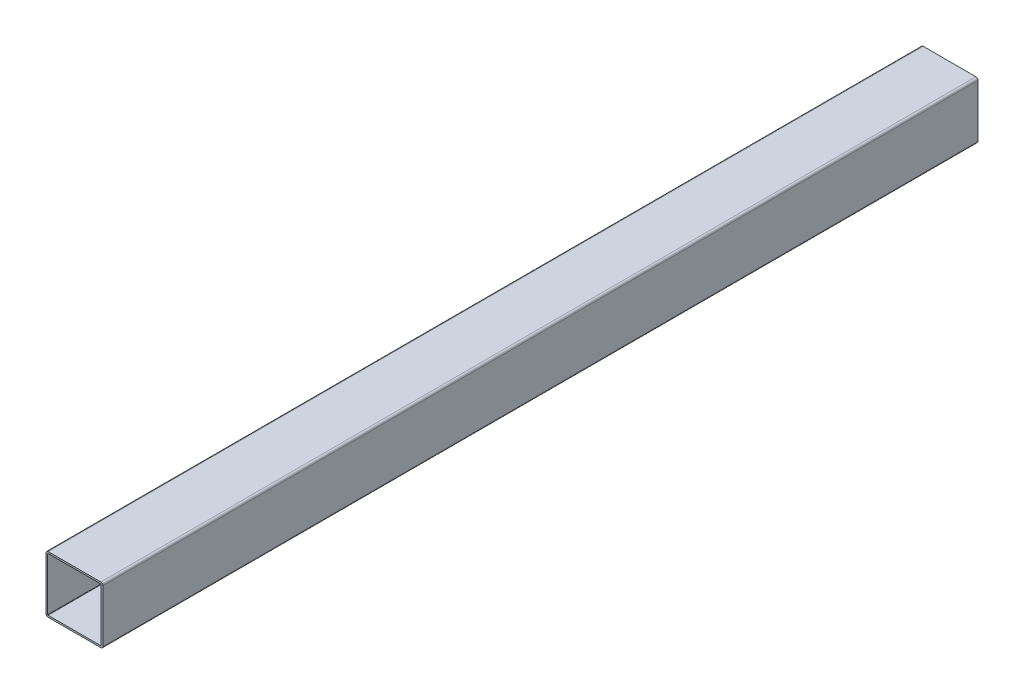
SolidWorks part; units mm, degrees
material "AISI 1020 Steel, Cold Rolled"
ref_plane "Front Plane" through (0, 0, 0) normal (0, 0, 1) x (1, 0, 0)
ref_plane "Top Plane" through (0, 0, 0) normal (0, 1, 0) x (1, 0, 0)
ref_plane "Right Plane" through (0, 0, 0) normal (1, 0, 0) x (0, 0, -1)
sketch "Sketch1" plane through (0, 0, 0) normal (0, 1, 0) x (1, 0, 0)
  line L0 (0, 0) -> (0, 615)
  dimension "D1" = 615
other "Structural Member1"
ref_plane "Plane1" through (0, 0, 0) normal (0, 0, -1) x (-1, 0, 0)
sketch "Sketch12" plane through (0, 0, 0) normal (0, 0, -1) x (-1, 0, 0)
  line L0 (-18.5, -18.8) -> (18.5, -18.8)
  line L1 (-18.8, -18.5) -> (-18.8, 18.5)
  line L2 (18.5, 18.8) -> (-18.5, 18.8)
  line L3 (18.8, 18.5) -> (18.8, -18.5)
  line L4 (-18.5, -20) -> (18.5, -20)
  line L5 (-20, -18.5) -> (-20, 18.5)
  line L6 (18.5, 20) -> (-18.5, 20)
  line L7 (20, 18.5) -> (20, -18.5)
  arc A0 (20, 18.5) -> (18.5, 20) centre (18.5, 18.5) ccw
  arc A1 (18.5, -20) -> (20, -18.5) centre (18.5, -18.5) ccw
  arc A2 (-20, -18.5) -> (-18.5, -20) centre (-18.5, -18.5) ccw
  arc A3 (-18.5, 20) -> (-20, 18.5) centre (-18.5, 18.5) ccw
  arc A4 (-18.5, 18.8) -> (-18.8, 18.5) centre (-18.5, 18.5) ccw
  arc A5 (18.8, 18.5) -> (18.5, 18.8) centre (18.5, 18.5) ccw
  arc A6 (18.5, -18.8) -> (18.8, -18.5) centre (18.5, -18.5) ccw
  arc A7 (-18.8, -18.5) -> (-18.5, -18.8) centre (-18.5, -18.5) ccw
  point P0 (-20, 0)
  point P1 (20, 0)
  point P2 (0, 20)
  point P3 (0, -20)
  point P4 (0, 0)
  point P5 (-20, -20)
  point P6 (20, -20)
  point P7 (20, 20)
  point P8 (-20, 20)
  point P33 (0, 0)
  dimension "D1" = 1.5
  dimension "Thickness" = 1.2
  dimension "V_leg" = 40
